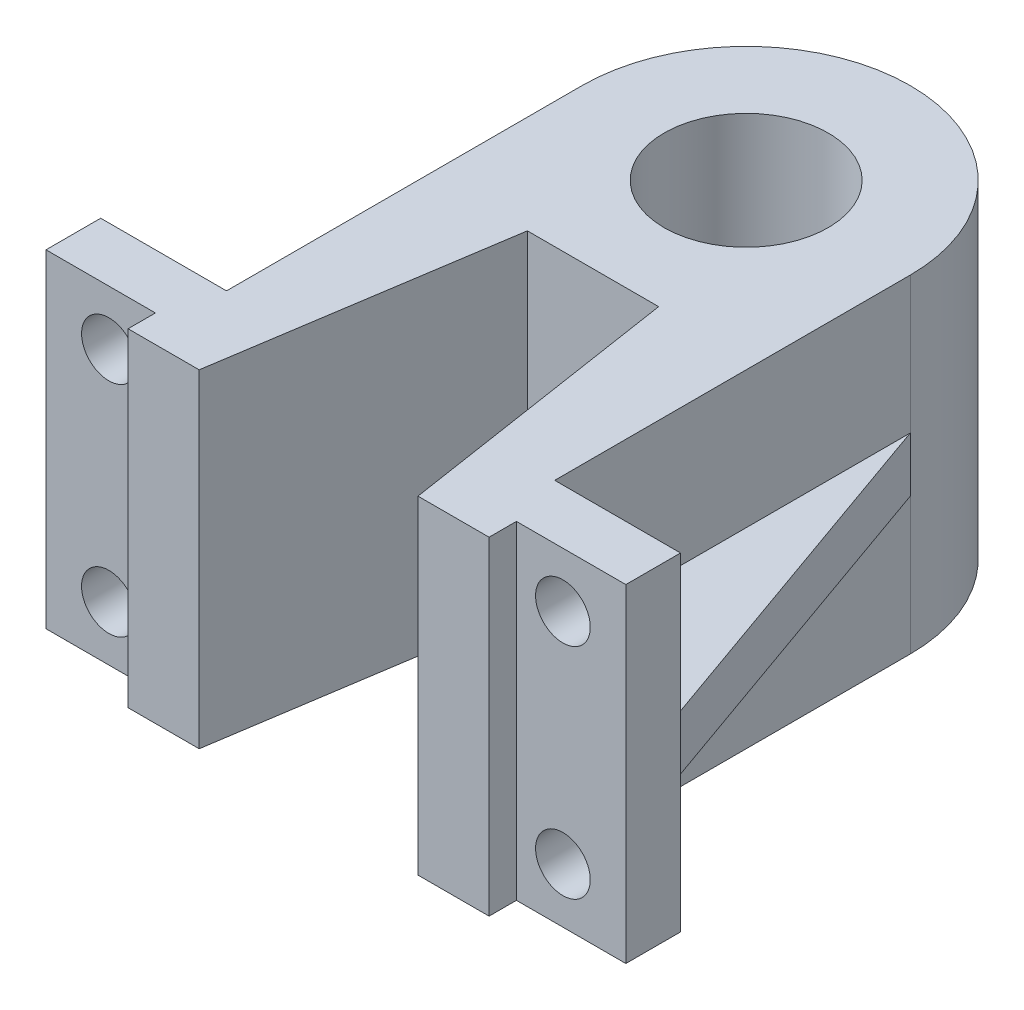
SolidWorks part; units mm, degrees
ref_plane "Front Plane" through (0, 0, 0) normal (0, 0, 1) x (1, 0, 0)
ref_plane "Top Plane" through (0, 0, 0) normal (0, 1, 0) x (1, 0, 0)
ref_plane "Right Plane" through (0, 0, 0) normal (1, 0, 0) x (0, 0, -1)
sketch "Sketch2" plane through (0, 0, 0) normal (0, 1, 0) x (1, 0, 0)
  line L0 (-12, -28) -> (12, -28)
  line L1 (-30, 0) -> (-30, -65)
  line L2 (30, 0) -> (30, -65)
  line L3 (-30, -65) -> (-53, -65)
  line L4 (-53, -65) -> (-53, -75)
  line L5 (-53, -75) -> (-33, -75)
  line L6 (-33, -75) -> (-33, -80)
  line L7 (-33, -80) -> (-20, -80)
  line L8 (-20, -80) -> (-12, -28)
  line L9 (30, -65) -> (53, -65)
  line L10 (0, -55) -> (0, 55) construction
  line L11 (33, -80) -> (20, -80)
  line L12 (33, -75) -> (33, -80)
  line L13 (53, -75) -> (33, -75)
  line L14 (20, -80) -> (12, -28)
  line L15 (30, -65) -> (53, -65)
  line L16 (53, -65) -> (53, -75)
  arc A0 (30, 0) -> (-30, 0) centre (0, 0) ccw
  circle A2 centre (0, 0) radius 15
  point P7 (0, -28)
  dimension "D1" = 60
  dimension "D2" = 30
  dimension "D3" = 28
  dimension "D4" = 24
  dimension "D5" = 10
  dimension "D6" = 40
  dimension "D7" = 66
  dimension "D8" = 106
  dimension "D9" = 5
  dimension "D10" = 75
extrude "Boss-Extrude1" add sketch "Sketch2" against normal blind 60 contours L2 A0 L1 L3 L4 L5 L6 L7 L8 L0 L14 L11 L12 L13 L16 L9 A2
sketch "Sketch3" plane through (0, 0, 65) normal (0, 0, -1) x (-1, 0, 0)
  line L0 (-30, 0) -> (-53, 0) construction
  line L1 (0, 33) -> (0, -33) construction
  circle A0 centre (-41.5, -10) radius 5
  circle A1 centre (41.5, -10) radius 5
  circle A2 centre (41.5, -50) radius 5
  circle A3 centre (-41.5, -50) radius 5
  dimension "D1" = 10
  dimension "D2" = 10
extrude "Cut-Extrude1" cut sketch "Sketch3" against normal blind 60
ref_plane "Plane2" through (0, -30, 0) normal (0, 1, 0) x (1, 0, 0)
sketch "Sketch7" plane through (0, -30, 0) normal (0, 1, 0) x (1, 0, 0)
  line L0 (30, 0) -> (53, -65)
rib "Rib1" sketch "Sketch7" sketch "Sketch7" thickness 10 extrusion direction parallel to sketch draft on no parameters "D1"=10
mirror "Mirror1" about plane through (0, 0, 0) normal (1, 0, 0) of "Rib1"
